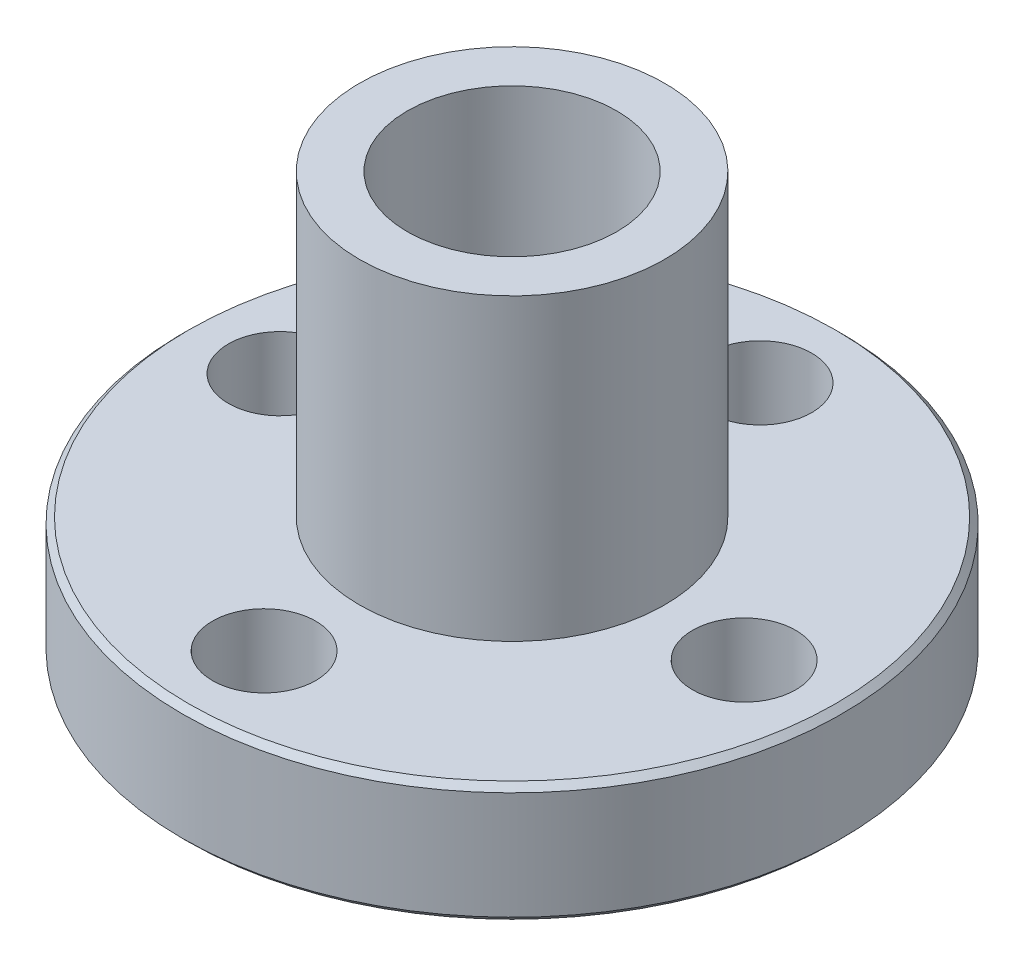
SolidWorks part; units mm, degrees
ref_plane "Front Plane" through (0, 0, 0) normal (0, 0, 1) x (1, 0, 0)
ref_plane "Top Plane" through (0, 0, 0) normal (0, 1, 0) x (1, 0, 0)
ref_plane "Right Plane" through (0, 0, 0) normal (1, 0, 0) x (0, 0, -1)
sketch "Sketch1" plane through (0, 0, 0) normal (0, 1, 0) x (1, 0, 0)
  circle A0 centre (0, 0) radius 11.013
  circle A1 centre (0, 0) radius 3.5
  dimension "D1" = 7
extrude "Boss-Extrude1" add sketch "Sketch1" along normal blind 4
sketch "Sketch2" plane through (0, 4, 0) normal (0, 1, 0) x (1, 0, 0)
  line L0 (0, 0) -> (8.0206, -0.2663) construction
  circle A0 centre (8.0206, -0.2663) radius 1.725
  circle A1 centre (-0.2663, -8.0206) radius 1.725
  circle A2 centre (-8.0206, 0.2663) radius 1.725
  circle A3 centre (0.2663, 8.0206) radius 1.725
  point P13 (0, 0)
  dimension "D1" = 3.45
  dimension "D2" = 4
extrude "Cut-Extrude1" cut sketch "Sketch2" against normal blind 4
sketch "Sketch3" plane through (0, 4, 0) normal (0, 1, 0) x (1, 0, 0)
  circle A0 centre (0, 0) radius 5.1
  circle A1 centre (0, 0) radius 3.5
  dimension "D1" = 10.2
extrude "Boss-Extrude2" add sketch "Sketch3" along normal blind 10
sketch "Sketch4" plane through (0, 0, 0) normal (0, -1, 0) x (-1, 0, 0)
  circle A0 centre (0, 0) radius 3.5
  circle A1 centre (0, 0) radius 5.125
  dimension "D1" = 10.25
extrude "Boss-Extrude3" add sketch "Sketch4" along normal blind 1.25
chamfer "Chamfer1" distance 0.2 angle 45 2 edges at (0, 0, 11.013) (0, 4, 11.013)
